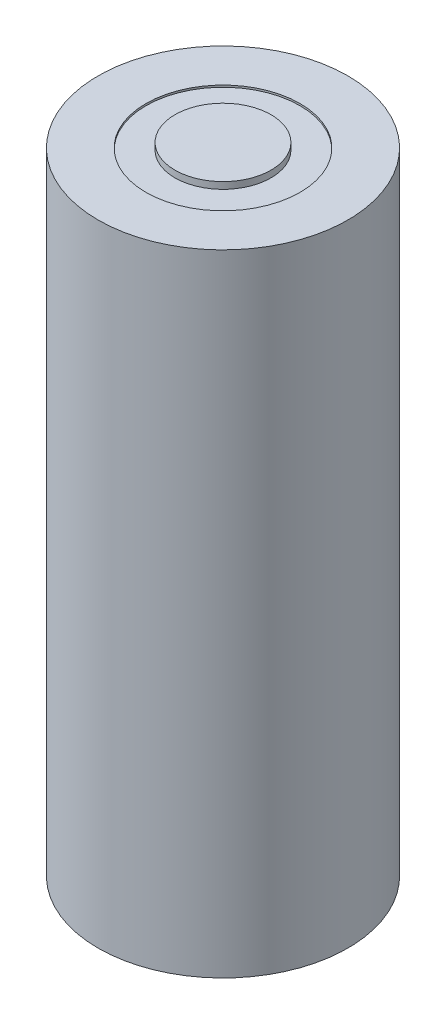
SolidWorks part; units mm, degrees
ref_plane "前视基准面" through (0, 0, 0) normal (0, 0, 1) x (1, 0, 0)
ref_plane "上视基准面" through (0, 0, 0) normal (0, 1, 0) x (1, 0, 0)
ref_plane "右视基准面" through (0, 0, 0) normal (1, 0, 0) x (0, 0, -1)
sketch "草图1" plane through (0, 0, 0) normal (0, 1, 0) x (1, 0, 0)
  circle A0 centre (0, 0) radius 13.05
  dimension "D1" = 26.1
extrude "凸台-拉伸1" add sketch "草图1" along normal blind 65.9
sketch "草图2" plane through (0, 0, 0) normal (0, -1, 0) x (1, 0, 0)
  circle A0 centre (0, 0) radius 10.9782
extrude "切除-拉伸1" cut sketch "草图2" against normal blind 0.5
sketch "草图3" plane through (0, 65.9, 0) normal (0, 1, 0) x (1, 0, 0)
  circle A0 centre (0, 0) radius 5.0217
extrude "凸台-拉伸2" add sketch "草图3" along normal blind 0.5
sketch "草图4" plane through (0, 65.9, 0) normal (0, 1, 0) x (1, 0, 0)
  circle A0 centre (0, 0) radius 5.0217
  circle A1 centre (0, 0) radius 8.0483
extrude "切除-拉伸2" cut sketch "草图4" against normal blind 0.2
